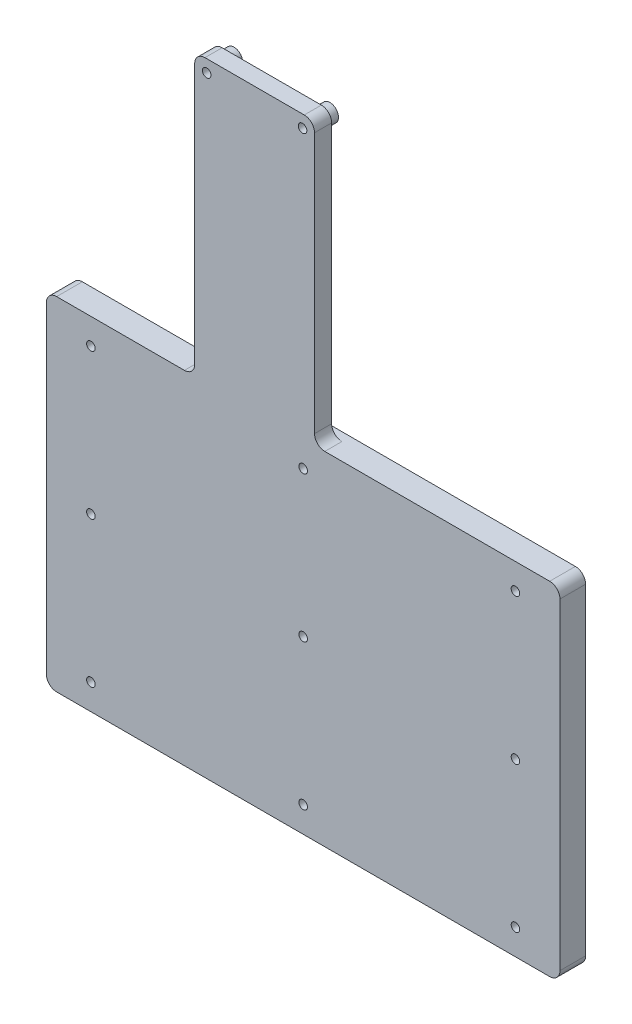
SolidWorks part; units mm, degrees
ref_plane "Plan de face" through (0, 0, 0) normal (0, 0, 1) x (1, 0, 0)
ref_plane "Plan de dessus" through (0, 0, 0) normal (0, 1, 0) x (1, 0, 0)
ref_plane "Plan de droite" through (0, 0, 0) normal (1, 0, 0) x (0, 0, -1)
sketch "Esquisse1" plane through (0, 0, 0) normal (0, 0, 1) x (1, 0, 0)
  line L0 (43.29, 103.0302) -> (43.29, 179.1302)
  line L5 (2.9684, 0.0302) -> (146.9684, 0.0302)
  line L6 (-0.0316, 3.0302) -> (-0.0316, 97.0302)
  line L7 (149.9684, 3.0302) -> (149.9684, 97.0302)
  line L8 (46.29, 182.1302) -> (75.29, 182.1302)
  line L9 (78.29, 179.1302) -> (78.29, 103.0302)
  line L10 (2.9684, 100.0302) -> (40.29, 100.0302)
  line L11 (81.29, 100.0302) -> (146.9684, 100.0302)
  arc A0 (2.9684, 0.0302) -> (-0.0316, 3.0302) centre (2.9684, 3.0302) cw
  arc A1 (146.9684, 0.0302) -> (149.9684, 3.0302) centre (146.9684, 3.0302) ccw
  arc A2 (146.9684, 100.0302) -> (149.9684, 97.0302) centre (146.9684, 97.0302) cw
  arc A3 (-0.0316, 97.0302) -> (2.9684, 100.0302) centre (2.9684, 97.0302) cw
  circle A4 centre (12.9684, 92.5302) radius 1.25
  circle A5 centre (74.9684, 92.5302) radius 1.25
  circle A6 centre (136.9684, 92.5302) radius 1.25
  circle A7 centre (12.9684, 50.0302) radius 1.25
  circle A8 centre (74.9684, 50.0302) radius 1.25
  circle A9 centre (136.9684, 50.0302) radius 1.25
  circle A10 centre (136.9684, 7.5302) radius 1.25
  circle A11 centre (74.9684, 7.5302) radius 1.25
  circle A12 centre (12.9684, 7.5302) radius 1.25
  arc A13 (43.29, 179.1302) -> (46.29, 182.1302) centre (46.29, 179.1302) cw
  arc A14 (75.29, 182.1302) -> (78.29, 179.1302) centre (75.29, 179.1302) cw
  arc A15 (78.29, 103.0302) -> (81.29, 100.0302) centre (81.29, 103.0302) ccw
  arc A16 (43.29, 103.0302) -> (40.29, 100.0302) centre (40.29, 103.0302) cw
  circle A17 centre (46.79, 178.5302) radius 1.25
  circle A18 centre (74.79, 178.5302) radius 1.25
  point P17 (-0.0316, 100.0302)
  dimension "D1" = 3
  dimension "D14" = 3
  dimension "D2" = 13
  dimension "D3" = 13
  dimension "D4" = 75
  dimension "D5" = 13
  dimension "D6" = 75
  dimension "D7" = 13
  dimension "D8" = 7.5
  dimension "D9" = 7.5
  dimension "D10" = 7.5
  dimension "D11" = 13
  dimension "D12" = 75
  dimension "D13" = 13
  dimension "D15" = 35
  dimension "D16" = 3.6
  dimension "D17" = 3.5
  dimension "D18" = 3.5
  dimension "D19" = 3.6
extrude "Boss.-Extru.1" add sketch "Esquisse1" along normal blind 8
sketch "Esquisse5" plane through (0, 0, 0) normal (0, 0, -1) x (-1, 0, 0)
  line L1 (-146.9684, 100.0302) -> (-81.29, 100.0302) construction
  line L3 (-83.7059, 100.0302) -> (-38.3883, 100.0302)
  line L4 (-83.7059, 100.0302) -> (-83.7059, 184.1318)
  line L5 (-83.7059, 184.1318) -> (-38.3883, 184.1318)
  line L6 (-38.3883, 100.0302) -> (-38.3883, 184.1318)
  circle A0 centre (-74.79, 178.5302) radius 2.5
  circle A1 centre (-46.79, 178.5302) radius 2.5
extrude "Enlèv. mat.-Extru.2" cut sketch "Esquisse5" against normal blind 3
sketch "Esquisse6" plane through (0, 0, 3) normal (0, 0, -1) x (-1, 0, 0)
  line L1 (-55.79, 165.5302) -> (-50.79, 165.5302)
  line L2 (-55.79, 165.5302) -> (-55.79, 103.5302)
  line L3 (-55.79, 103.5302) -> (-50.79, 103.5302)
  line L4 (-50.79, 165.5302) -> (-50.79, 103.5302)
  line L5 (-43.29, 179.1302) -> (-43.29, 103.0302) construction
  circle A0 centre (-46.79, 178.5302) radius 1.25 construction
  dimension "D3" = 13
  dimension "D1" = 62
  dimension "D2" = 5
  dimension "D4" = 7.5
extrude "Boss.-DC/DC" add sketch "Esquisse6" along normal blind 2
sketch "Esquisse7" plane through (0, 0, 3) normal (0, 0, -1) x (-1, 0, 0)
  line L0 (-74.79, 178.5302) -> (-74.79, 163.8807) construction
  line L1 (-73.79, 167.5302) -> (-65.79, 167.5302)
  line L2 (-75.79, 165.5302) -> (-75.79, 107.5302)
  line L3 (-73.79, 105.5302) -> (-65.79, 105.5302)
  line L4 (-63.79, 165.5302) -> (-63.79, 107.5302)
  circle A0 centre (-74.79, 178.5302) radius 1.25 construction
  arc A1 (-75.79, 107.5302) -> (-73.79, 105.5302) centre (-73.79, 107.5302) ccw
  arc A2 (-65.79, 105.5302) -> (-63.79, 107.5302) centre (-65.79, 107.5302) ccw
  arc A3 (-65.79, 167.5302) -> (-63.79, 165.5302) centre (-65.79, 165.5302) cw
  arc A4 (-73.79, 167.5302) -> (-75.79, 165.5302) centre (-73.79, 165.5302) ccw
  dimension "D1" = 11
  dimension "D2" = 12
  dimension "D4" = 2
  dimension "D3" = 1
  dimension "D5" = 62
extrude "Enlèv. Inductors" cut sketch "Esquisse7" against normal blind 2
sketch "Esquisse8" plane through (0, 0, 0) normal (0, 0, -1) x (-1, 0, 0)
  line L1 (-152.3488, -1.5345) -> (2.412, -1.5345)
  line L2 (-152.3488, -1.5345) -> (-152.3488, 101.72)
  line L3 (-152.3488, 101.72) -> (2.412, 101.72)
  line L4 (2.412, -1.5345) -> (2.412, 101.72)
extrude "Enlèv. mat.-Extru.3" cut sketch "Esquisse8" against normal blind 0.5
